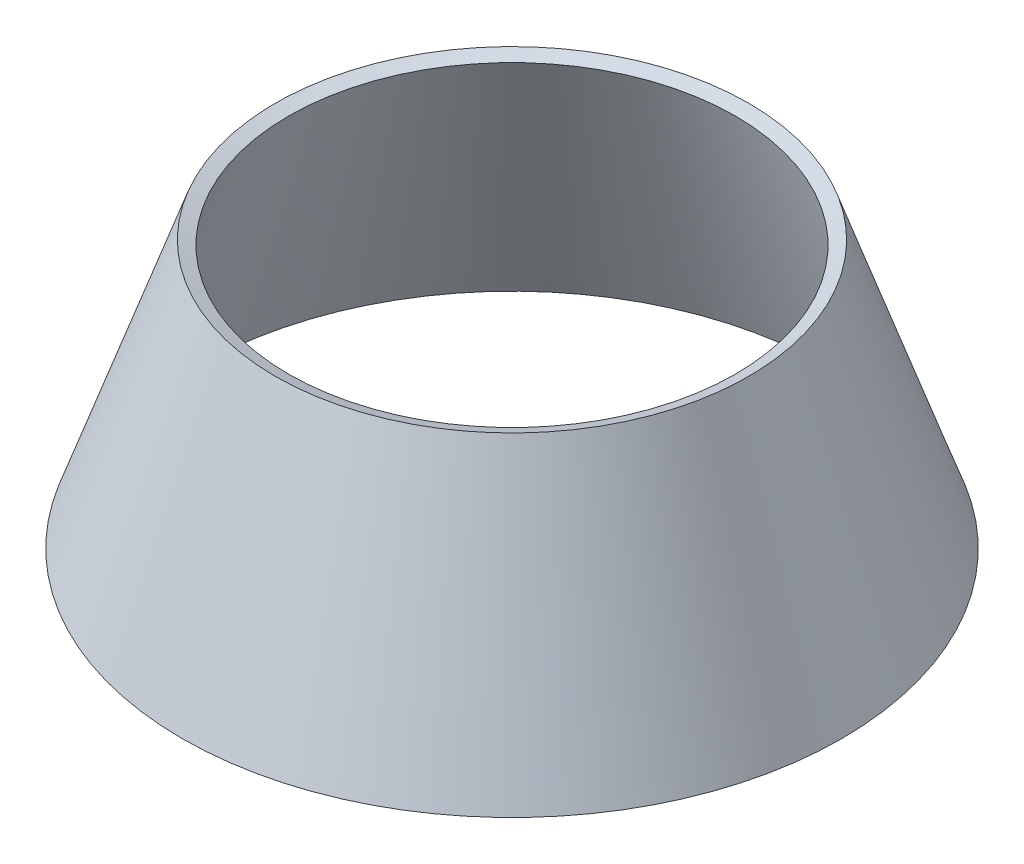
SolidWorks part; units mm, degrees
ref_plane "Plan1" through (0, 0, 0) normal (0, 0, 1) x (1, 0, 0)
ref_plane "Plan2" through (0, 0, 0) normal (0, 1, 0) x (1, 0, 0)
ref_plane "Plan3" through (0, 0, 0) normal (1, 0, 0) x (0, 0, -1)
sketch "Esquisse2" plane through (0, 0, 0) normal (1, 0, 0) x (0, 0, -1)
  line L0 (-24.5038, -48.8064) -> (-17.8199, -68)
  line L1 (-41.5, 0) -> (-17.8199, -68) construction
  line L2 (-41.5, -110) -> (-41.5, -90) construction
  line L4 (-41.5, -125) -> (-41.5, 125) construction
revolve "Base-Révol.-Mince" add sketch "Esquisse2" angle 360 about L2
sketch "Esquisse3" plane through (0, 0, 0) normal (1, 0, 0) x (0, 0, -1)
  line L0 (-65.1801, -68) -> (-17.8199, -68)
  line L1 (-65.1801, -68) -> (-64.2357, -68.3289) construction
  line L3 (-18.7643, -68.3289) -> (-17.8199, -68) construction
  line L4 (-17.8199, -68) -> (-65.1801, -68) construction
  line L5 (-17.8199, -68) -> (-17.8199, -68.3289)
  line L6 (-17.8199, -68.3289) -> (-65.1801, -68.3289)
  line L7 (-65.1801, -68.3289) -> (-65.1801, -68)
  line L8 (-18.7643, -68.3289) -> (-64.2357, -68.3289) construction
extrude "Enlèv. mat.-Extru.1" cut sketch "Esquisse3" against normal through all and the other way through all
sketch "sommet pignon" plane through (0, 0, 0) normal (1, 0, 0) x (0, 0, -1)
  line L2 (-17.8199, -68) -> (-24.5038, -48.8064) construction
  line L3 (-58.4962, -48.8064) -> (-65.1801, -68) construction
  point P0 (-41.5, 0)
